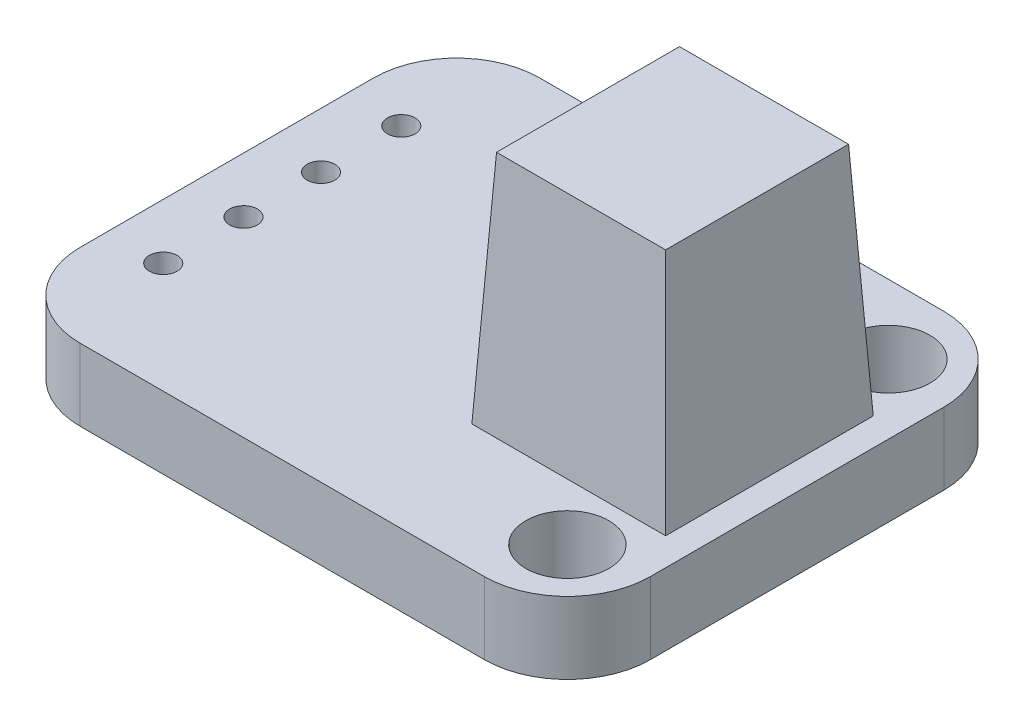
SolidWorks part; units mm, degrees
ref_plane "Front Plane" through (0, 0, 0) normal (0, 0, 1) x (1, 0, 0)
ref_plane "Top Plane" through (0, 0, 0) normal (0, 1, 0) x (1, 0, 0)
ref_plane "Right Plane" through (0, 0, 0) normal (1, 0, 0) x (0, 0, -1)
sketch "Sketch1" plane through (0, 0, 0) normal (0, 1, 0) x (1, 0, 0)
  line L1 (-10.3, -8.3) -> (10.3, -8.3)
  line L2 (-10.3, -8.3) -> (-10.3, 8.3)
  line L3 (-10.3, 8.3) -> (10.3, 8.3)
  line L4 (10.3, -8.3) -> (10.3, 8.3)
  line L5 (-10.3, -8.3) -> (10.3, 8.3) construction
  line L6 (-10.3, 8.3) -> (10.3, -8.3) construction
  point P0 (0, 0)
  dimension "D1" = 16.6
  dimension "D2" = 20.6
extrude "Boss-Extrude1" add sketch "Sketch1" along normal blind 2.6
fillet "Fillet1" radius 3 4 edges at (-10.3, 1.3, -8.3) (-10.3, 1.3, 8.3) (10.3, 1.3, -8.3) (10.3, 1.3, 8.3)
sketch "Sketch2" plane through (0, 2.6, 0) normal (0, 1, 0) x (1, 0, 0)
  line L0 (7.3, 8.3) -> (-7.3, 8.3) construction
  line L1 (10.3, -5.3) -> (10.3, 5.3) construction
  line L2 (-7.3, -8.3) -> (7.3, -8.3) construction
  circle A0 centre (7.8, 5.8) radius 1.5
  circle A1 centre (7.8, -5.8) radius 1.5
  dimension "D1" = 3
  dimension "D2" = 3
  dimension "D3" = 2.5
  dimension "D4" = 2.5
  dimension "D5" = 2.5
extrude "Cut-Extrude1" cut sketch "Sketch2" against normal blind 2.6
sketch "Sketch3" plane through (0, 2.6, 0) normal (0, 1, 0) x (1, 0, 0)
  line L1 (2.3, 3.75) -> (9.3, 3.75)
  line L2 (2.3, 3.75) -> (2.3, -3.75)
  line L3 (2.3, -3.75) -> (9.3, -3.75)
  line L4 (9.3, 3.75) -> (9.3, -3.75)
  line L5 (2.3, 3.75) -> (9.3, -3.75) construction
  line L6 (2.3, -3.75) -> (9.3, 3.75) construction
  line L8 (10.3, -5.3) -> (10.3, 5.3) construction
  point P0 (5.8, 0)
  dimension "D1" = 7.5
  dimension "D2" = 7
  dimension "D3" = 1
extrude "Boss-Extrude2" add sketch "Sketch3" along normal blind 8.5 draft 3
sketch "Sketch4" plane through (0, 2.6, 0) normal (0, 1, 0) x (1, 0, 0)
  line L0 (7.3, 8.3) -> (-7.3, 8.3) construction
  line L1 (-7.3, -8.3) -> (7.3, -8.3) construction
  line L3 (-10.3, 5.3) -> (-10.3, -5.3) construction
  circle A0 centre (-8.3, 4.3) radius 0.5
  circle A3 centre (-8.3, -4.3) radius 0.5
  circle A4 centre (-8.3, -1.4) radius 0.5
  circle A5 centre (-8.3, 1.4) radius 0.5
  dimension "D3" = 1
  dimension "D4" = 1
  dimension "D7" = 1
  dimension "D8" = 1
  dimension "D1" = 4
  dimension "D2" = 4
  dimension "D5" = 2.9
  dimension "D6" = 2.9
  dimension "D9" = 2
extrude "Cut-Extrude2" cut sketch "Sketch4" against normal blind 8.5
